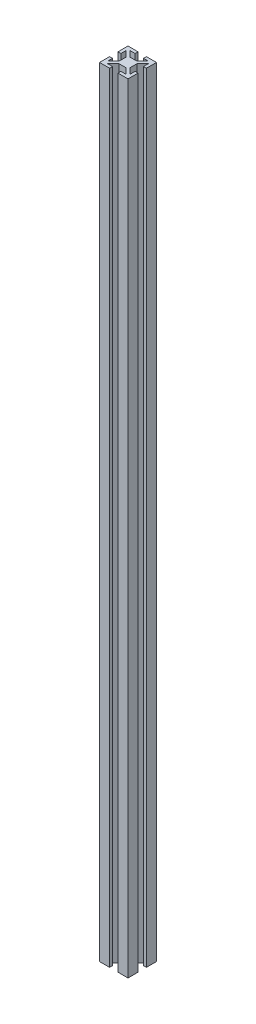
SolidWorks part; units mm, degrees
ref_plane "Front Plane" through (0, 0, 0) normal (0, 0, 1) x (1, 0, 0)
ref_plane "Top Plane" through (0, 0, 0) normal (0, 1, 0) x (1, 0, 0)
ref_plane "Right Plane" through (0, 0, 0) normal (1, 0, 0) x (0, 0, -1)
other "Configuration Table"
sketch "Sketch1" plane through (0, 0, 0) normal (0, 1, 0) x (1, 0, 0)
  line L13 (0, 13.925) -> (0, -13.925) construction
  line L14 (-13.925, -13.925) -> (-4.1, -13.925)
  line L19 (-13.925, -13.925) -> (-13.925, -4.1)
  line L20 (-13.925, 13.925) -> (-4.1, 13.925)
  line L34 (13.925, -13.925) -> (13.925, -4.1)
  line L41 (-13.925, -13.925) -> (13.925, 13.925) construction
  line L42 (-13.925, 13.925) -> (13.925, -13.925) construction
  line L43 (4.1, 13.925) -> (4.1, 11.04)
  line L44 (-13.925, 0) -> (13.925, 0) construction
  line L45 (4.1, 11.04) -> (9, 11.04)
  line L46 (9, 11.04) -> (3.445, 5.485)
  line L47 (3.445, 5.485) -> (-3.445, 5.485)
  line L48 (5.485, 3.445) -> (5.485, -3.445)
  line L49 (11.04, 9) -> (5.485, 3.445)
  line L50 (11.04, 4.1) -> (11.04, 9)
  line L51 (13.925, 4.1) -> (11.04, 4.1)
  line L52 (9, 11.04) -> (11.04, 9) construction
  line L53 (3.445, -5.485) -> (-3.445, -5.485)
  line L54 (4.1, -13.925) -> (4.1, -11.04)
  line L55 (4.1, -11.04) -> (9, -11.04)
  line L56 (9, -11.04) -> (3.445, -5.485)
  line L57 (13.925, -4.1) -> (11.04, -4.1)
  line L58 (11.04, -4.1) -> (11.04, -9)
  line L59 (11.04, -9) -> (5.485, -3.445)
  line L60 (-9, -11.04) -> (-3.445, -5.485)
  line L61 (-4.1, -11.04) -> (-9, -11.04)
  line L62 (-4.1, -13.925) -> (-4.1, -11.04)
  line L63 (-13.925, -4.1) -> (-11.04, -4.1)
  line L64 (-11.04, -4.1) -> (-11.04, -9)
  line L65 (-11.04, -9) -> (-5.485, -3.445)
  line L66 (-5.485, 3.445) -> (-5.485, -3.445)
  line L67 (-11.04, 9) -> (-5.485, 3.445)
  line L68 (-13.925, 4.1) -> (-11.04, 4.1)
  line L69 (-11.04, 4.1) -> (-11.04, 9)
  line L70 (-9, 11.04) -> (-3.445, 5.485)
  line L71 (-4.1, 11.04) -> (-9, 11.04)
  line L72 (-4.1, 13.925) -> (-4.1, 11.04)
  line L73 (-13.925, 0) -> (-13.925, 4.1) construction
  line L74 (-13.925, 4.1) -> (-13.925, 13.925)
  line L75 (-13.925, -4.1) -> (-13.925, 0) construction
  line L76 (-4.1, -13.925) -> (0, -13.925) construction
  line L77 (4.1, -13.925) -> (13.925, -13.925)
  line L78 (0, -13.925) -> (4.1, -13.925) construction
  line L79 (13.925, -4.1) -> (13.925, 0) construction
  line L80 (13.925, 4.1) -> (13.925, 13.925)
  line L81 (13.925, 0) -> (13.925, 4.1) construction
  line L82 (0, 13.925) -> (4.1, 13.925) construction
  line L83 (4.1, 13.925) -> (13.925, 13.925)
  line L84 (-4.1, 13.925) -> (0, 13.925) construction
  point P0 (0, 0)
  point P30 (5.485, 0)
  point P31 (0, -5.485)
  point P43 (0, 5.485)
  dimension "D3" = 8.44
  dimension "D1" = 27.85
  dimension "D2" = 18
  dimension "D4" = 8.2
extrude "Boss-Extrude1" add sketch "Sketch1" along normal blind 762
equation "\"length\"= 0in"
equation "\"D1@Boss-Extrude1\"=\"ActualLength\""
equation "\"ActualLength\"= 30in"
